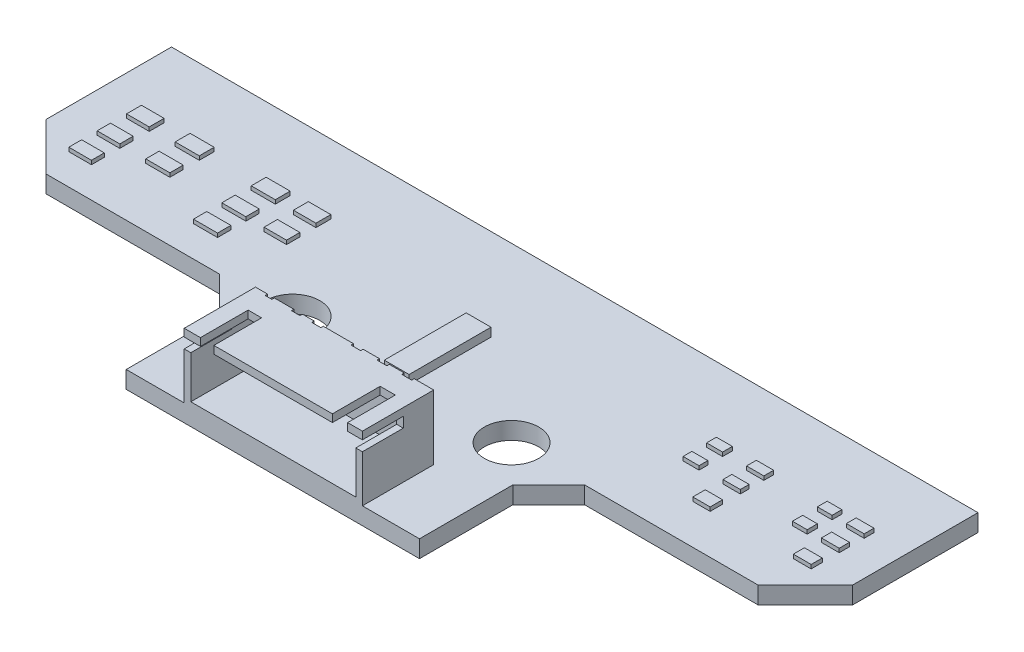
SolidWorks part; units mm, degrees
ref_plane "前视基准面" through (0, 0, 0) normal (0, 0, 1) x (1, 0, 0)
ref_plane "上视基准面" through (0, 0, 0) normal (0, 1, 0) x (1, 0, 0)
ref_plane "右视基准面" through (0, 0, 0) normal (1, 0, 0) x (0, 0, -1)
sketch "草图2" plane through (0, 0, 0) normal (0, 1, 0) x (1, 0, 0)
  line L7 (-46.75, 0) -> (46.75, 0)
  line L8 (-17, -35) -> (17, -35)
  line L9 (17, -35) -> (17, -24.1719)
  line L10 (17, -24.1719) -> (21.1563, -20.0156)
  line L11 (21.1563, -20.0156) -> (41.2813, -20.0156)
  line L12 (41.2813, -20.0156) -> (46.75, -14.5469)
  line L13 (46.75, -14.5469) -> (46.75, 0)
  line L14 (-41.2813, -20.0156) -> (-46.75, -14.5469)
  line L15 (-21.1562, -20.0156) -> (-41.2813, -20.0156)
  line L16 (-17, -24.1719) -> (-21.1562, -20.0156)
  line L17 (-17, -35) -> (-17, -24.1719)
  line L18 (-46.75, -14.5469) -> (-46.75, 0)
  circle A0 centre (12.6875, -20.0156) radius 3.1549
  circle A1 centre (-12.6875, -20.0156) radius 3.1549
extrude "凸台-拉伸1" add sketch "草图2" along normal blind 2
sketch "草图3" plane through (0, 2, 0) normal (0, 1, 0) x (1, 0, 0)
  line L0 (-10.2732, -35) -> (-10.2732, -26.735)
  line L1 (-17, -35) -> (17, -35) construction
  line L2 (-10.2732, -26.735) -> (10.3825, -26.735)
  line L3 (10.3825, -26.735) -> (10.3825, -35)
  line L4 (-10.2732, -35) -> (10.3825, -35)
extrude "凸台-拉伸2" add sketch "草图3" along normal blind 0.5
sketch "草图5" plane through (-10.2732, 0, 0) normal (-1, 0, 0) x (0, 0, 1)
  line L0 (26.735, 2.5) -> (26.735, 7.2434)
  line L1 (26.735, 2.5) -> (35, 2.5) construction
  line L2 (26.735, 7.2434) -> (35, 7.2434)
  line L3 (35, 7.2434) -> (35, 6.1797)
  line L4 (35, 6.1797) -> (30.8675, 6.1797)
  line L5 (30.8675, 6.1797) -> (30.8675, 5.157)
  line L6 (30.8675, 5.157) -> (35, 5.157)
  line L7 (35, 5.157) -> (35, 2.5)
  line L8 (35, 2.5) -> (26.735, 2.5)
extrude "凸台-拉伸5" add sketch "草图5" along normal blind 0.5 separate body contours L8 L0 L2 L3 L4 L5 L6 L7
sketch "草图6" plane through (-10.2732, 0, 0) normal (1, 0, 0) x (0, 0, -1)
  line L6 (-35, 7.2434) -> (-26.735, 7.2434)
  line L7 (-26.735, 7.2434) -> (-26.735, 6.8332)
  line L8 (-26.735, 2.5) -> (-26.735, 7.2434) construction
  line L9 (-26.735, 6.8332) -> (-35, 6.8332)
  line L10 (-35, 7.2434) -> (-35, 6.1797) construction
  line L11 (-35, 6.8332) -> (-35, 7.2434)
extrude "凸台-拉伸6" add sketch "草图6" along normal blind 20
sketch "草图11" plane through (0, 7.2434, 0) normal (0, 1, 0) x (1, 0, 0)
  line L0 (-10.7732, -26.735) -> (-10.7732, -35)
  line L1 (-10.7732, -26.735) -> (9.7268, -26.735) construction
  line L2 (-10.7732, -26.735) -> (-10.7732, -35) construction
  line L3 (-10.7732, -35) -> (9.7268, -35)
  line L4 (-10.7732, -35) -> (9.7268, -35) construction
  line L5 (9.7268, -35) -> (9.7268, -26.735)
  line L6 (9.7268, -26.735) -> (-10.7732, -26.735)
extrude "切除-拉伸1" cut sketch "草图11" against normal blind 0.5
sketch "草图12" plane through (-10.7732, 0, 0) normal (-1, 0, 0) x (0, 0, 1)
  line L0 (26.735, 6.7434) -> (35, 6.7434)
  line L1 (35, 6.7434) -> (35, 6.1741)
  line L2 (35, 6.1741) -> (30.8675, 6.1797)
  line L3 (35, 6.1797) -> (30.8675, 6.1797) construction
  line L4 (30.8675, 6.1797) -> (30.8675, 5.157)
  line L5 (30.8675, 5.157) -> (35, 5.157)
  line L6 (35, 5.157) -> (35, 2.5)
  line L7 (35, 2.5) -> (26.735, 2.5)
  line L8 (26.735, 2.5) -> (26.735, 6.7434)
extrude "切除-拉伸2" cut sketch "草图12" against normal blind 0.5
sketch "草图13" plane through (0, 2.5, 0) normal (0, 1, 0) x (1, 0, 0)
  line L0 (-10.2732, -35) -> (-10.2732, -26.735)
  line L1 (-10.2732, -26.735) -> (-9.5082, -26.735)
  line L2 (10.3825, -26.735) -> (-10.2732, -26.735) construction
  line L3 (-9.5082, -26.735) -> (-9.5082, -35)
  line L4 (-10.2732, -35) -> (10.3825, -35) construction
  line L5 (-9.5082, -35) -> (-10.2732, -35)
extrude "凸台-拉伸13" add sketch "草图13" along normal blind 7
sketch "草图14" plane through (-10.2732, 0, 0) normal (-1, 0, 0) x (0, 0, 1)
  line L0 (35, 8.616) -> (30.2641, 8.616)
  line L2 (35, 9.5) -> (35, 2) construction
  line L3 (30.2641, 8.616) -> (30.2641, 7.4296)
  line L4 (30.2641, 7.4296) -> (35, 7.4296)
  line L5 (35, 7.4296) -> (35, 8.616)
extrude "切除-拉伸3" cut sketch "草图14" against normal blind 7
sketch "草图16" plane through (-9.5082, 0, 0) normal (1, 0, 0) x (0, 0, -1)
  line L0 (-35, 9.5) -> (-26.735, 9.5)
  line L1 (-26.735, 9.5) -> (-26.735, 8.616)
  line L2 (-26.735, 9.5) -> (-26.735, 2.5) construction
  line L3 (-26.735, 8.616) -> (-35, 8.616)
  line L4 (-35, 8.616) -> (-35, 9.5)
extrude "凸台-拉伸14" add sketch "草图16" along normal blind 19.89
sketch "草图18" plane through (0, 2.5, 0) normal (0, 1, 0) x (1, 0, 0)
  line L0 (10.3825, -35) -> (10.3825, -26.735)
  line L1 (10.3825, -26.735) -> (-9.5082, -26.735) construction
  line L2 (10.3825, -35) -> (10.3825, -26.735) construction
sketch "草图20" plane through (0, 2.5, 0) normal (0, 1, 0) x (1, 0, 0)
  line L0 (10.3825, -35) -> (10.3825, -26.735)
  line L1 (10.3825, -26.735) -> (9.6175, -26.735)
  line L3 (10.3825, -26.735) -> (-9.5082, -26.735) construction
  line L5 (9.6175, -26.735) -> (9.6175, -35)
  line L6 (-9.5082, -35) -> (10.3825, -35) construction
  line L7 (9.6175, -35) -> (10.3825, -35)
  dimension "D1" = 0.765
extrude "凸台-拉伸15" add sketch "草图20" along normal blind 7
sketch "草图23" plane through (10.3825, 0, 0) normal (1, 0, 0) x (0, 0, -1)
  line L0 (-35, 2.5) -> (-35, 7.43)
  line L1 (-35, 9.5) -> (-35, 2) construction
  line L2 (-35, 7.43) -> (-30.26, 7.43)
sketch "草图25" plane through (10.3825, 0, 0) normal (1, 0, 0) x (0, 0, -1)
  line L1 (-35, 9.5) -> (-35, 2) construction
  line L5 (-30.26, 8.62) -> (-30.26, 7.43)
  line L6 (-30.26, 8.62) -> (-35, 8.62)
  line L7 (-35, 7.43) -> (-35, 8.62)
  line L8 (-35, 7.43) -> (-30.26, 7.43)
extrude "切除-拉伸4" cut sketch "草图25" against normal blind 7
sketch "草图26" plane through (0, 9.5, 0) normal (0, 1, 0) x (1, 0, 0)
  line L0 (-8.3949, -35) -> (-8.3949, -29.4693)
  line L1 (-10.2732, -35) -> (10.3825, -35) construction
  line L2 (-8.3949, -29.4693) -> (-6.8357, -29.4693)
  line L3 (-6.8357, -29.4693) -> (-6.8357, -35)
  line L4 (-6.8357, -35) -> (-8.3949, -35)
extrude "切除-拉伸5" cut sketch "草图26" against normal blind 1
sketch "草图27" plane through (0, 9.5, 0) normal (0, 1, 0) x (1, 0, 0)
  line L0 (8.6694, -35) -> (8.6694, -29.4693)
  line L1 (-6.8357, -35) -> (10.3825, -35) construction
  line L2 (8.6694, -29.4693) -> (6.9081, -29.4693)
  line L3 (6.9081, -29.4693) -> (6.9081, -35)
  line L4 (6.9081, -35) -> (8.6694, -35)
extrude "切除-拉伸6" cut sketch "草图27" against normal blind 1
sketch "草图28" plane through (0, 2.5, 0) normal (0, 1, 0) x (1, 0, 0)
  line L0 (9.6175, -26.735) -> (9.6175, -27.4109)
  line L1 (9.6175, -26.735) -> (9.6175, -35) construction
  line L2 (9.6175, -26.735) -> (-9.5082, -26.735)
  line L3 (9.6175, -27.4109) -> (-9.5082, -27.2261)
  line L4 (-9.5082, -27.2261) -> (-9.5082, -26.735)
extrude "凸台-拉伸16" add sketch "草图28" along normal blind 7
sketch "草图29" plane through (0, 9.5, 0) normal (0, 1, 0) x (1, 0, 0)
  line L0 (-8.8642, -26.735) -> (-8.8642, -27.0212)
  line L1 (10.3825, -26.735) -> (-10.2732, -26.735) construction
  line L2 (-8.8642, -27.0212) -> (-8.0941, -27.0212)
  line L3 (-8.0941, -27.0212) -> (-8.0941, -26.735)
  line L4 (-8.0941, -26.735) -> (-8.8642, -26.735)
  line L14 (-5.8241, -26.735) -> (-5.8241, -27.0212)
  line L15 (-5.8241, -27.0212) -> (-4.831, -27.0212)
  line L16 (-4.831, -27.0212) -> (-4.831, -26.735)
  line L17 (-4.831, -26.735) -> (-5.8241, -26.735)
  line L18 (-3.4731, -26.735) -> (-3.4731, -27.0212)
  line L19 (10.3825, -26.735) -> (-10.2732, -26.735) construction
  line L20 (-3.4731, -27.0212) -> (-2.4192, -27.0212)
  line L21 (-2.4192, -27.0212) -> (-2.4192, -26.735)
  line L22 (-2.4192, -26.735) -> (-3.4731, -26.735)
  line L23 (1.0871, -26.735) -> (1.0871, -27.0212)
  line L24 (1.0871, -27.0212) -> (2.2018, -27.0212)
  line L25 (2.2018, -27.0212) -> (2.2018, -26.735)
  line L26 (2.2018, -26.735) -> (1.0871, -26.735)
  line L27 (4.0867, -26.735) -> (4.0867, -27.0212)
  line L28 (4.0867, -27.0212) -> (5.2419, -27.0212)
  line L29 (5.2419, -27.0212) -> (5.2419, -26.735)
  line L30 (5.2419, -26.735) -> (4.0867, -26.735)
  line L31 (6.9647, -26.735) -> (6.9647, -27.0212)
  line L32 (6.9647, -27.0212) -> (8.1199, -27.0212)
  line L33 (8.1199, -27.0212) -> (8.1199, -26.735)
  line L34 (8.1199, -26.735) -> (6.9647, -26.735)
extrude "切除-拉伸7" cut sketch "草图29" against normal blind 10
sketch "草图30" plane through (0, 2, 0) normal (0, 1, 0) x (1, 0, 0)
  line L0 (-1.9761, -20.1049) -> (-1.9761, -10.611)
  line L1 (-1.9761, -10.611) -> (0.9026, -10.611)
  line L2 (0.9026, -10.611) -> (0.9026, -20.1049)
  line L3 (0.9026, -20.1049) -> (-1.9761, -20.1049)
extrude "凸台-拉伸17" add sketch "草图30" along normal blind 1
sketch "草图31" plane through (0, 2, 0) normal (0, 1, 0) x (1, 0, 0)
  line L0 (40.6625, -8.0386) -> (42.7289, -8.0386)
  line L1 (42.7289, -8.0386) -> (42.7289, -9.1751)
  line L2 (42.7289, -9.1751) -> (40.6625, -9.1751)
  line L3 (40.6625, -9.1751) -> (40.6625, -8.0386)
  line L4 (40.6625, -10.8798) -> (42.7289, -10.8798)
  line L5 (42.7289, -10.8798) -> (42.7289, -12.068)
  line L6 (42.7289, -12.068) -> (40.6625, -12.068)
  line L7 (40.6625, -12.068) -> (40.6625, -10.8798)
  line L8 (40.6625, -14.0311) -> (42.7289, -14.0311)
  line L9 (42.7289, -14.0311) -> (42.7289, -15.3225)
  line L10 (42.7289, -15.3225) -> (40.6625, -15.3225)
  line L11 (40.6625, -15.3225) -> (40.6625, -14.0311)
  line L12 (39.0094, -8.0386) -> (39.0094, -9.1751)
  line L13 (39.0094, -9.1751) -> (37.3046, -9.1751)
  line L14 (37.3046, -9.1751) -> (37.3046, -8.0386)
  line L15 (37.3046, -8.0386) -> (39.0094, -8.0386)
  line L16 (39.0094, -10.8798) -> (39.0094, -12.068)
  line L17 (39.0094, -12.068) -> (37.3046, -12.068)
  line L18 (37.3046, -12.068) -> (37.3046, -10.8798)
  line L19 (37.3046, -10.8798) -> (39.0094, -10.8798)
extrude "凸台-拉伸18" add sketch "草图31" along normal blind 0.45
sketch "草图32" plane through (0, 2, 0) normal (0, 1, 0) x (1, 0, 0)
  line L0 (31.0993, -8.0386) -> (31.0993, -9.1751)
  line L1 (31.0993, -9.1751) -> (29.0927, -9.1751)
  line L2 (29.0927, -9.1751) -> (29.0927, -8.0386)
  line L3 (29.0927, -8.0386) -> (31.0993, -8.0386)
  line L4 (31.0993, -10.8798) -> (31.0993, -11.9049)
  line L5 (31.0993, -11.9049) -> (29.0927, -11.9049)
  line L6 (29.0927, -11.9049) -> (29.0927, -10.8798)
  line L7 (29.0927, -10.8798) -> (31.0993, -10.8798)
  line L8 (31.0993, -13.963) -> (31.0993, -15.4037)
  line L9 (31.0993, -15.4037) -> (29.0927, -15.4037)
  line L10 (29.0927, -15.4037) -> (29.0927, -13.963)
  line L11 (29.0927, -13.963) -> (31.0993, -13.963)
  line L12 (26.3142, -8.0386) -> (26.3142, -9.1751)
  line L13 (26.3142, -9.1751) -> (24.4619, -9.1751)
  line L14 (24.4619, -9.1751) -> (24.4619, -8.0386)
  line L15 (24.4619, -8.0386) -> (25.8511, -8.0386)
  line L16 (25.8511, -8.0386) -> (26.3142, -8.0386)
  line L17 (26.3142, -10.8798) -> (26.3142, -11.9049)
  line L18 (26.3142, -11.9049) -> (24.4619, -11.9049)
  line L19 (24.4619, -11.9049) -> (24.4619, -10.8798)
  line L20 (24.4619, -10.8798) -> (26.3142, -10.8798)
extrude "凸台-拉伸19" add sketch "草图32" along normal blind 0.45
sketch "草图33" plane through (0, 2, 0) normal (0, 1, 0) x (1, 0, 0)
  line L0 (-20.2396, -8.0386) -> (-20.2396, -9.7652)
  line L1 (-22.8432, -9.7652) -> (-22.8432, -8.0386)
  line L2 (-22.8432, -8.0386) -> (-20.2396, -8.0386)
  line L3 (-22.8432, -9.7652) -> (-20.2396, -9.7652)
  line L4 (-20.2396, -11.6249) -> (-22.8432, -11.6249)
  line L5 (-22.8432, -11.6249) -> (-22.8432, -13.1747)
  line L6 (-22.8432, -13.1747) -> (-20.2396, -13.1747)
  line L7 (-20.2396, -13.1747) -> (-20.2396, -11.6249)
  line L8 (-20.2396, -14.9725) -> (-22.8432, -14.9725)
  line L9 (-22.8432, -14.9725) -> (-22.8432, -16.4602)
  line L10 (-22.8432, -16.4602) -> (-20.2396, -16.4602)
  line L11 (-20.2396, -16.4602) -> (-20.2396, -14.9725)
  line L12 (-24.9509, -8.0386) -> (-24.9509, -9.7652)
  line L13 (-24.9509, -9.7652) -> (-27.7405, -9.7652)
  line L14 (-27.7405, -9.7652) -> (-27.7405, -8.0386)
  line L15 (-27.7405, -8.0386) -> (-25.8188, -8.0386)
  line L16 (-25.8188, -8.0386) -> (-24.9509, -8.0386)
  line L18 (-24.9509, -13.1747) -> (-27.7405, -13.1747)
  line L19 (-27.7405, -13.1747) -> (-27.7405, -11.6249)
  line L22 (-33.7623, -8.0386) -> (-33.7623, -9.7652)
  line L23 (-33.7623, -9.7652) -> (-36.5584, -9.7652)
  line L24 (-36.5584, -9.7652) -> (-36.5584, -8.0386)
  line L25 (-36.5584, -8.0386) -> (-33.7623, -8.0386)
  line L26 (-33.7623, -11.6249) -> (-36.5584, -11.6249)
  line L27 (-36.5584, -11.6249) -> (-36.5584, -13.1747)
  line L28 (-36.5584, -13.1747) -> (-33.7623, -13.1747)
  line L29 (-33.7623, -13.1747) -> (-33.7623, -11.6249)
  line L30 (-33.7623, -14.9725) -> (-33.7623, -16.4602)
  line L31 (-33.7623, -16.4602) -> (-36.5584, -16.4602)
  line L32 (-36.5584, -16.4602) -> (-36.5584, -14.9725)
  line L33 (-36.5584, -14.9725) -> (-33.7623, -14.9725)
  line L34 (-39.5663, -8.0386) -> (-39.5663, -9.7652)
  line L35 (-39.5663, -9.7652) -> (-42.1929, -9.7652)
  line L36 (-42.1929, -9.7652) -> (-42.1929, -8.0386)
  line L37 (-42.1929, -8.0386) -> (-39.5663, -8.0386)
  line L38 (-39.5663, -11.6249) -> (-39.5663, -13.1747)
  line L42 (-39.5663, -14.9725) -> (-39.5663, -16.4602)
  line L43 (-39.5663, -16.4602) -> (-42.1929, -16.4602)
  line L44 (-42.1929, -16.4602) -> (-42.1929, -14.9725)
  line L45 (-42.1929, -14.9725) -> (-39.5663, -14.9725)
  line L46 (-39.5663, -11.6249) -> (-42.1929, -11.6249)
  line L47 (-42.1929, -11.6249) -> (-42.1929, -13.1747)
  line L48 (-42.1929, -13.1747) -> (-39.5663, -13.1747)
  line L49 (-27.7405, -11.6249) -> (-24.9509, -11.6249)
  line L50 (-24.9509, -11.6249) -> (-24.9509, -13.1747)
extrude "凸台-拉伸20" add sketch "草图33" along normal blind 0.45
sketch "草图34" plane through (0, 2, 0) normal (0, 1, 0) x (1, 0, 0)
  circle A0 centre (-8.4862, -26.8732) radius 0.1026
  circle A1 centre (-5.303, -26.8732) radius 0.1138
  circle A2 centre (-2.9394, -26.8732) radius 0.1176
  circle A3 centre (1.6533, -26.8732) radius 0.104
  circle A4 centre (4.7429, -26.8732) radius 0.1099
  circle A5 centre (7.5438, -26.8732) radius 0.0802
extrude "凸台-拉伸21" add sketch "草图34" along normal blind 4 separate body
sketch "草图35" plane through (0, 9.5, 0) normal (0, 1, 0) x (1, 0, 0)
  line L0 (-8.4862, -26.9758) -> (-8.4862, -35)
  line L1 (-10.2732, -35) -> (-8.3949, -35) construction
  line L2 (-5.1892, -26.8732) -> (-5.1892, -35)
  line L3 (-6.8357, -35) -> (6.9081, -35) construction
  line L4 (-2.8218, -26.8732) -> (-2.8218, -35)
  line L5 (1.6533, -26.9772) -> (1.6533, -35)
  line L6 (4.8528, -26.8732) -> (4.8528, -35)
  line L7 (7.5423, -27.0212) -> (7.5423, -35)
  line L8 (6.9647, -27.0212) -> (8.1199, -27.0212) construction
  line L9 (-9.5082, -35) -> (9.6175, -35) construction
  circle A0 centre (-8.4862, -26.8732) radius 0.1026 construction
  circle A1 centre (-5.303, -26.8732) radius 0.1138 construction
  circle A2 centre (-2.9394, -26.8732) radius 0.1176 construction
  circle A3 centre (1.6533, -26.8732) radius 0.104 construction
  circle A4 centre (4.7429, -26.8732) radius 0.1099 construction
sketch "草图36" plane through (-0.2639, 0, 27.3154) normal (-0.0097, 0, 1) x (1, 0, 0.0097)
  circle A0 centre (-8.1682, 7.3874) radius 0.1349
  circle A1 centre (-4.9109, 7.3874) radius 0.1621
  circle A2 centre (-2.6389, 7.3874) radius 0.1821
  circle A3 centre (1.9052, 7.3874) radius 0.1608
  circle A4 centre (5.0648, 7.3874) radius 0.1632
  circle A5 centre (7.7855, 7.3874) radius 0.1953
extrude "凸台-拉伸22" add sketch "草图36" along normal blind 5.5
sketch "草图39" plane through (0, 2.45, 0) normal (0, 1, 0) x (1, 0, 0)
  line L0 (-36.5584, -14.9725) -> (-33.7623, -14.9725)
  line L1 (-33.7623, -14.9725) -> (-33.7623, -16.4602)
  line L2 (-33.7623, -16.4602) -> (-36.5584, -16.4602)
  line L3 (-36.5584, -16.4602) -> (-36.5584, -14.9725)
extrude "切除-拉伸8" cut sketch "草图39" against normal blind 0.45
sketch "草图40" plane through (0, 2.45, 0) normal (0, 1, 0) x (1, 0, 0)
  line L0 (-22.8432, -14.9725) -> (-20.2396, -14.9725)
  line L1 (-20.2396, -14.9725) -> (-20.2396, -16.4602)
  line L2 (-20.2396, -16.4602) -> (-22.8432, -16.4602)
  line L3 (-22.8432, -16.4602) -> (-20.2396, -16.4602) construction
  line L4 (-22.8432, -14.9725) -> (-22.8432, -16.4602) construction
  line L5 (-22.8432, -16.4602) -> (-22.8432, -14.9725)
extrude "切除-拉伸9" cut sketch "草图40" against normal blind 0.45
sketch "草图41" plane through (0, 2, 0) normal (0, 1, 0) x (1, 0, 0)
  line L0 (-27.7405, -14.9178) -> (-24.9509, -14.9178)
  line L1 (-24.9509, -14.9178) -> (-24.9509, -16.4602)
  line L2 (-24.9509, -16.4602) -> (-27.7405, -16.4602)
  line L3 (-27.7405, -16.4602) -> (-27.7405, -14.9178)
extrude "凸台-拉伸23" add sketch "草图41" along normal blind 0.45
